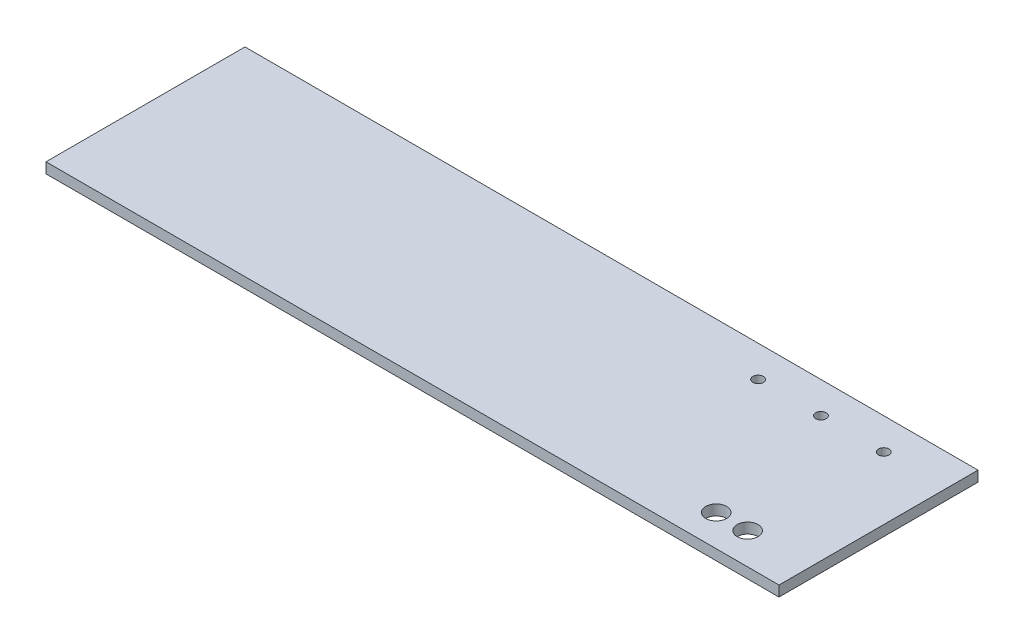
SolidWorks part; units mm, degrees
ref_plane "Alzado" through (0, 0, 0) normal (0, 0, 1) x (1, 0, 0)
ref_plane "Planta" through (0, 0, 0) normal (0, 1, 0) x (1, 0, 0)
ref_plane "Vista lateral" through (0, 0, 0) normal (1, 0, 0) x (0, 0, -1)
sketch "Croquis1" plane through (0, 0, 0) normal (0, 1, 0) x (1, 0, 0)
  line L1 (-350, -95) -> (350, -95)
  line L2 (-350, -95) -> (-350, 95)
  line L3 (-350, 95) -> (350, 95)
  line L4 (350, -95) -> (350, 95)
  line L5 (-350, -95) -> (350, 95) construction
  line L6 (-350, 95) -> (350, -95) construction
  point P0 (0, 0)
  dimension "D1" = 700
  dimension "D2" = 190
extrude "Saliente-Extruir1" add sketch "Croquis1" along normal blind 10
sketch "Croquis2" plane through (0, 10, 0) normal (0, 1, 0) x (1, 0, 0)
  line L0 (350, -95) -> (350, 95) construction
  line L1 (-350, -95) -> (350, -95) construction
  line L2 (350, 95) -> (-350, 95) construction
  circle A0 centre (290, 65) radius 5
  circle A1 centre (230, 65) radius 5
  circle A2 centre (170, 65) radius 5
  circle A3 centre (290, -65) radius 10
  circle A4 centre (260, -65) radius 10
  dimension "D1" = 60
  dimension "D2" = 30
  dimension "D3" = 30
  dimension "D4" = 60
  dimension "D5" = 60
  dimension "D6" = 60
  dimension "D7" = 30
extrude "Cortar-Extruir1" cut sketch "Croquis2" against normal up to surface (10 mm away) up to face at (0, 0, 0)
